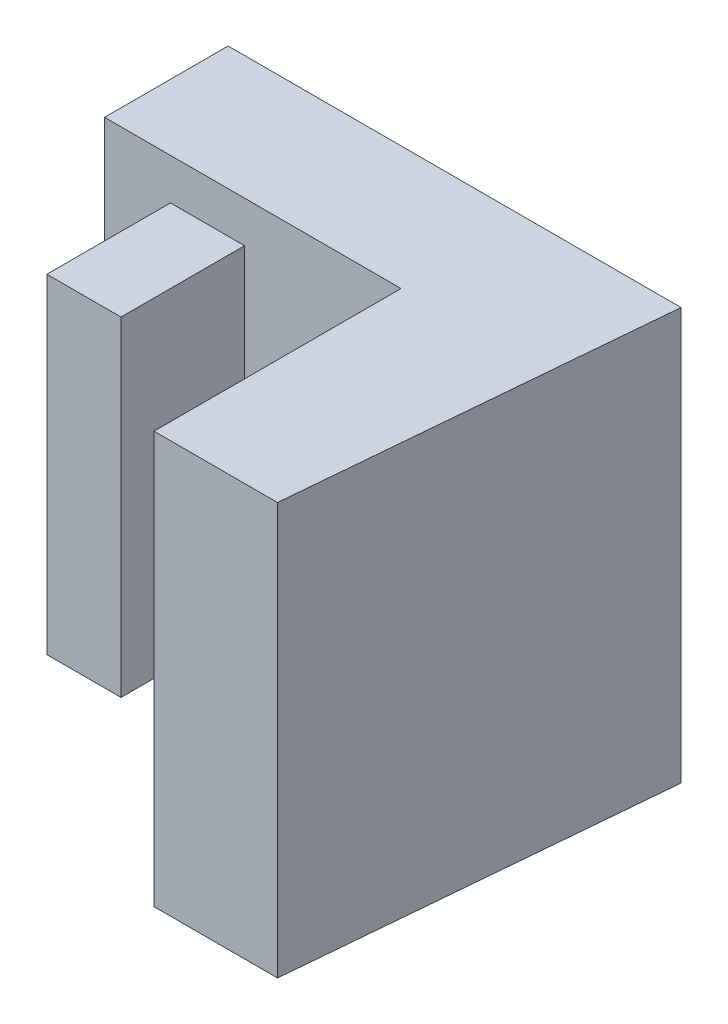
SolidWorks part; units mm, degrees
ref_plane "Front Plane" through (0, 0, 0) normal (0, 0, 1) x (1, 0, 0)
ref_plane "Top Plane" through (0, 0, 0) normal (0, 1, 0) x (1, 0, 0)
ref_plane "Right Plane" through (0, 0, 0) normal (1, 0, 0) x (0, 0, -1)
sketch "Sketch1" plane through (0, 0, 0) normal (0, 1, 0) x (1, 0, 0)
  line L0 (0, 0) -> (7.2, 0)
  line L1 (7.2, 0) -> (7.2, -6)
  line L2 (7.2, -6) -> (10.2, -6)
  line L3 (10.2, -6) -> (11, 3)
  line L4 (11, 3) -> (0, 3)
  line L5 (0, 3) -> (0, 0)
  dimension "D1" = 6
  dimension "D2" = 3
  dimension "D3" = 7.2
  dimension "D4" = 3
  dimension "D5" = 11
extrude "Boss-Extrude1" add sketch "Sketch1" along normal blind 10
sketch "Sketch2" plane through (0, 0, 0) normal (0, 0, 1) x (1, 0, 0)
  line L0 (0, 10) -> (0, 0) construction
  line L1 (1.6, 9) -> (3.4, 9)
  line L2 (1.6, 9) -> (1.6, 1)
  line L3 (1.6, 1) -> (3.4, 1)
  line L4 (3.4, 9) -> (3.4, 1)
  line L5 (0, 0) -> (7.2, 0) construction
  line L6 (0, 10) -> (7.2, 10) construction
  dimension "D1" = 1.6
  dimension "D2" = 1.8
  dimension "D3" = 1
  dimension "D4" = 1
extrude "Boss-Extrude2" add sketch "Sketch2" along normal blind 3
